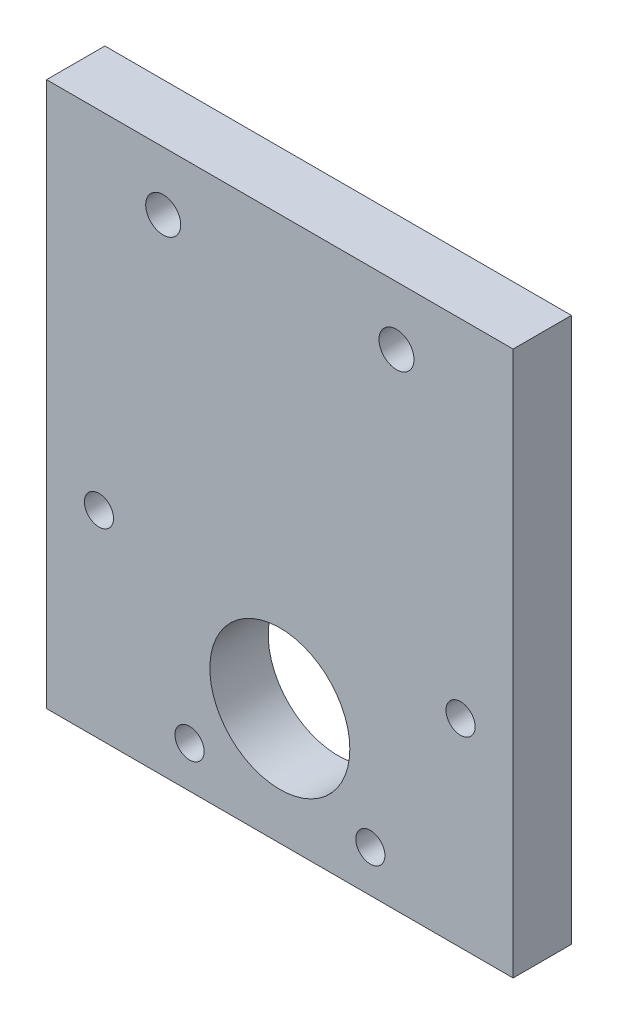
SolidWorks part; units mm, degrees
material "Cast Alloy Steel"
ref_plane "Front Plane" through (0, 0, 0) normal (0, 0, 1) x (1, 0, 0)
ref_plane "Top Plane" through (0, 0, 0) normal (0, 1, 0) x (1, 0, 0)
ref_plane "Right Plane" through (0, 0, 0) normal (1, 0, 0) x (0, 0, -1)
sketch "Sketch1" plane through (0, 0, 0) normal (0, 0, 1) x (1, 0, 0)
  line L0 (40, 17.1429) -> (0, 17.1429) construction
  line L1 (0, -2.8571) -> (40, -2.8571)
  line L2 (0, -2.8571) -> (0, 37.1429)
  line L3 (0, 33.707) -> (40, 33.8409) construction
  line L4 (40, -2.8571) -> (40, 37.1429)
  line L5 (0, 17.1429) -> (20, 17.1429) construction
  line L6 (20, 17.1429) -> (20, -2.8571) construction
  line L7 (20, -2.8571) -> (20, 7.1429) construction
  line L8 (20, 7.1429) -> (0, 7.1429) construction
  line L9 (65.3533, 33.8409) -> (-102.9127, 33.8409) construction
  line L10 (20, 43.8409) -> (20, 33.7739) construction
  line L11 (0, 37.1429) -> (0, 43.8409)
  line L12 (0, 43.8409) -> (40, 43.8409)
  line L13 (40, 37.1429) -> (40, 43.8409)
  line L14 (20, 38.8074) -> (0, 38.8074) construction
  circle A0 centre (20, 7.1429) radius 6
  circle A1 centre (4.4915, 14.124) radius 1.25
  circle A2 centre (12.2578, 0.71) radius 1.25
  circle A3 centre (27.7578, 0.7289) radius 1.25
  circle A4 centre (35.4915, 14.1617) radius 1.25
  circle A5 centre (10, 38.8074) radius 1.5
  circle A6 centre (30, 38.8074) radius 1.5
  dimension "D2" = 12
  dimension "D3" = 2.5
  dimension "D4" = 2.5
  dimension "D5" = 2.5
  dimension "D6" = 2.5
  dimension "D7" = 3
  dimension "D1" = 40
extrude "Boss-Extrude1" add sketch "Sketch1" along normal blind 5
